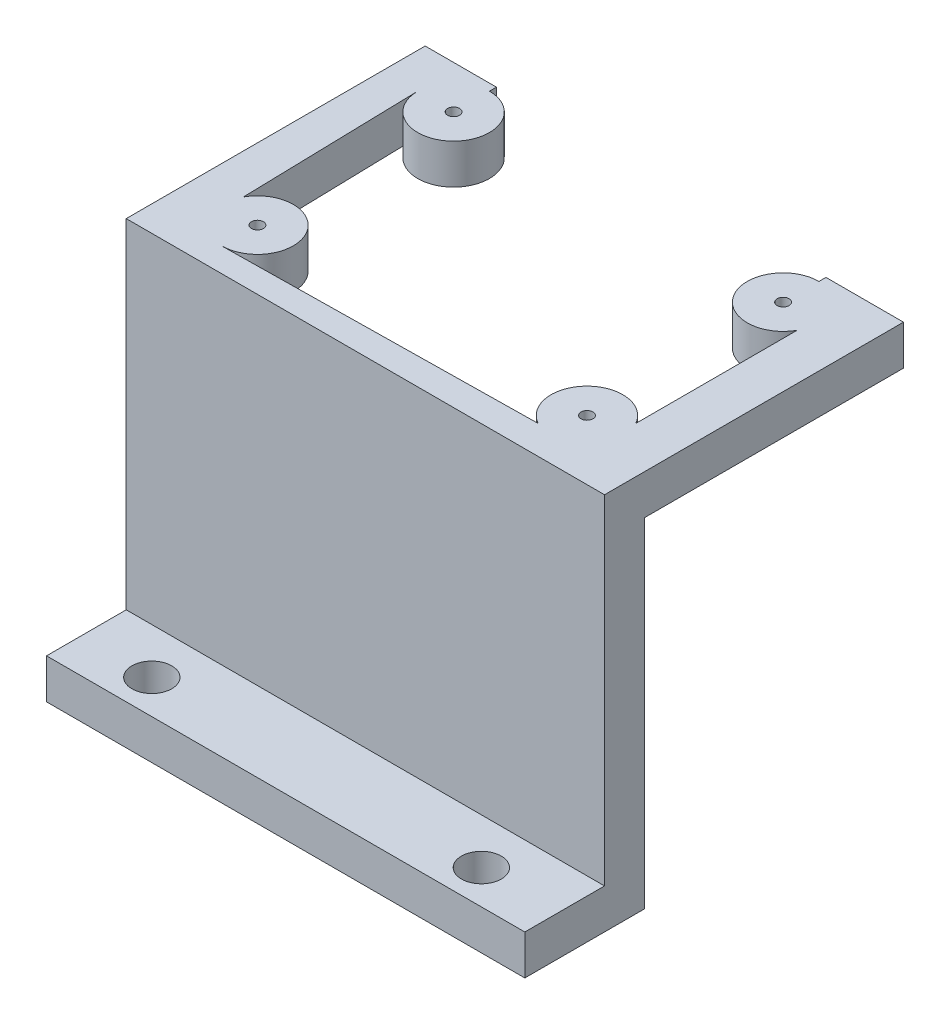
SolidWorks part; units mm, degrees
ref_plane "Front Plane" through (0, 0, 0) normal (0, 0, 1) x (1, 0, 0)
ref_plane "Top Plane" through (0, 0, 0) normal (0, 1, 0) x (1, 0, 0)
ref_plane "Right Plane" through (0, 0, 0) normal (1, 0, 0) x (0, 0, -1)
sketch "Sketch1" plane through (0, 0, 0) normal (1, 0, 0) x (0, 0, -1)
  line L0 (0, 0) -> (7.62, 0)
  line L1 (7.62, 0) -> (7.62, 21.59)
  line L2 (7.62, 21.59) -> (24.13, 21.59)
  line L3 (24.13, 21.59) -> (24.13, 24.13)
  line L4 (24.13, 24.13) -> (5.08, 24.13)
  line L5 (5.08, 24.13) -> (5.08, 2.54)
  line L6 (5.08, 2.54) -> (0, 2.54)
  line L7 (0, 2.54) -> (0, 0)
  line L8 (7.62, 21.59) -> (5.08, 21.59) construction
  dimension "D1" = 2.54
  dimension "D2" = 2.54
  dimension "D3" = 2.54
  dimension "D4" = 7.62
  dimension "D5" = 21.59
  dimension "D6" = 19.05
extrude "Boss-Extrude1" add sketch "Sketch1" along normal blind 30.48
sketch "Sketch2" plane through (0, 24.13, 0) normal (0, 1, 0) x (1, 0, 0)
  line L0 (2.2547, 21.3425) -> (2.54, 10.0072)
  line L1 (2.54, 30.9) -> (2.54, 6.9) construction
  line L2 (4.5729, 6.6142) -> (24.4328, 6.9)
  line L3 (2.54, 6.9) -> (27.54, 6.9) construction
  line L4 (27.54, 20.2928) -> (27.54, 10.0072)
  line L5 (27.54, 6.9) -> (27.54, 30.9) construction
  line L6 (4.54, 23.686) -> (4.54, 25.8453)
  line L7 (4.54, 25.8453) -> (25.54, 25.5814)
  line L8 (25.54, 25.5814) -> (25.54, 23.686)
  arc A0 (2.2547, 21.3425) -> (4.54, 23.686) centre (4.54, 21.4) ccw
  arc A1 (25.54, 23.686) -> (27.54, 20.2928) centre (25.54, 21.4) ccw
  arc A2 (27.54, 10.0072) -> (24.4328, 6.9) centre (25.54, 8.9) ccw
  arc A3 (4.5729, 6.6142) -> (2.54, 10.0072) centre (4.54, 8.9) ccw
  dimension "D1" = 4.572
extrude "Cut-Extrude1" cut sketch "Sketch2" against normal blind 2.54
sketch "Sketch3" plane through (0, 24.13, 0) normal (0, 1, 0) x (1, 0, 0)
  circle A0 centre (4.54, 8.9) radius 0.381
  circle A1 centre (4.54, 21.4) radius 0.381
  circle A2 centre (25.54, 21.4) radius 0.381
  circle A3 centre (25.54, 8.9) radius 0.381
  circle A4 centre (4.54, 2.1698) radius 1.27
  circle A5 centre (25.54, 2.1698) radius 1.27
  dimension "D1" = 0.762
  dimension "D2" = 2.54
extrude "Cut-Extrude2" cut sketch "Sketch3" against normal blind 30.48
